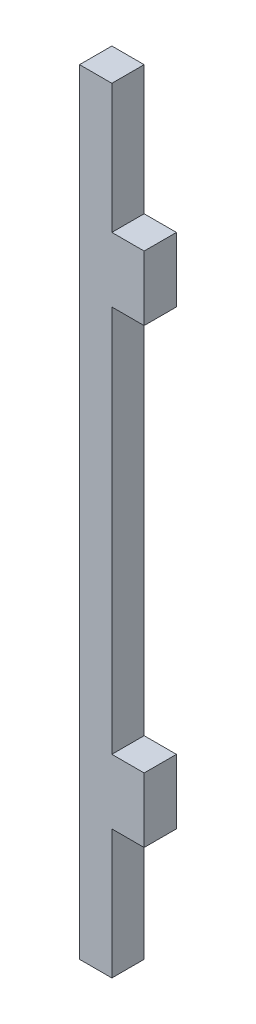
SolidWorks part; units mm, degrees
ref_plane "Plan de face" through (0, 0, 0) normal (0, 0, 1) x (1, 0, 0)
ref_plane "Plan de dessus" through (0, 0, 0) normal (0, 1, 0) x (1, 0, 0)
ref_plane "Plan de droite" through (0, 0, 0) normal (1, 0, 0) x (0, 0, -1)
sketch "Esquisse1" plane through (0, 0, 0) normal (0, 0, 1) x (1, 0, 0)
  line L0 (0, 60) -> (24.8211, 60) construction
  line L1 (0, 0) -> (-5, 0)
  line L2 (0, 0) -> (0, 20)
  line L3 (0, 120) -> (-5, 120)
  line L4 (-5, 0) -> (-5, 120)
  line L5 (0, 100) -> (5, 100)
  line L6 (0, 30) -> (0, 90)
  line L7 (0, 90) -> (5, 90)
  line L8 (5, 100) -> (5, 90)
  line L9 (0, 20) -> (5, 20)
  line L11 (0, 30) -> (5, 30)
  line L12 (5, 20) -> (5, 30)
  line L13 (0, 100) -> (0, 120)
  dimension "D1" = 120
  dimension "D2" = 5
  dimension "D3" = 5
  dimension "D4" = 20
  dimension "D5" = 10
extrude "Boss.-Extru.1" add sketch "Esquisse1" along normal blind 5
